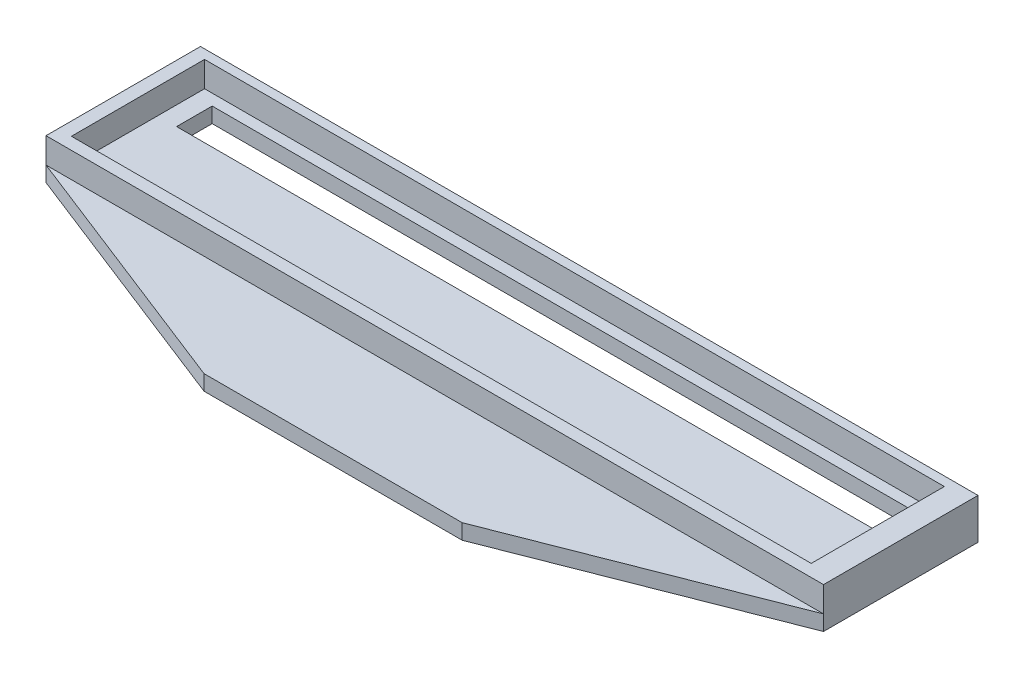
SolidWorks part; units mm, degrees
ref_plane "Alzado" through (0, 0, 0) normal (0, 0, 1) x (1, 0, 0)
ref_plane "Planta" through (0, 0, 0) normal (0, 1, 0) x (1, 0, 0)
ref_plane "Vista lateral" through (0, 0, 0) normal (1, 0, 0) x (0, 0, -1)
sketch "Croquis1" plane through (0, 0, 0) normal (0, 1, 0) x (1, 0, 0)
  line L1 (-38.25, 7.6) -> (38.25, 7.6)
  line L2 (-38.25, 7.6) -> (-38.25, -7.6)
  line L3 (-38.25, -7.6) -> (38.25, -7.6)
  line L4 (38.25, 7.6) -> (38.25, -7.6)
  line L5 (-38.25, 7.6) -> (38.25, -7.6) construction
  line L6 (-38.25, -7.6) -> (38.25, 7.6) construction
  point P0 (0, 0)
  dimension "D1" = 15.2
  dimension "D2" = 76.5
extrude "Saliente-Extruir1" add sketch "Croquis1" along normal blind 4
sketch "Croquis2" plane through (0, 4, 0) normal (0, 1, 0) x (1, 0, 0)
  line L0 (38.25, 7.6) -> (-38.25, 7.6) construction
  line L1 (-38.25, 7.6) -> (-38.25, -7.6) construction
  line L2 (38.25, -7.6) -> (38.25, 7.6) construction
  line L3 (-35.1, 5.6) -> (35.1, 5.6)
  line L4 (-35.1, 5.6) -> (-35.1, 2.1)
  line L5 (-35.1, 2.1) -> (35.1, 2.1)
  line L6 (35.1, 5.6) -> (35.1, 2.1)
  point P6 (0, 0)
  dimension "D1" = 2
  dimension "D2" = 3.5
  dimension "D3" = 3.15
  dimension "D4" = 3.15
extrude "Cortar-Extruir1" cut sketch "Croquis2" against normal blind 4
sketch "Croquis3" plane through (0, 4, 0) normal (0, 1, 0) x (1, 0, 0)
  line L0 (-35.1, 5.6) -> (-35.1, 2.1) construction
  line L1 (-36.95, 6.7) -> (35.8421, 6.7)
  line L2 (-36.95, 6.7) -> (-36.95, -6.4)
  line L3 (-36.95, -6.4) -> (35.8421, -6.4)
  line L4 (35.8421, 6.7) -> (35.8421, -6.4)
  line L5 (35.1, 5.6) -> (-35.1, 5.6) construction
  line L6 (-35.1, 2.1) -> (35.1, 2.1) construction
  dimension "D1" = 1.85
  dimension "D2" = 1.1
  dimension "D3" = 8.5
extrude "Cortar-Extruir2" cut sketch "Croquis3" against normal blind 2.5
sketch "Croquis4" plane through (0, 0, 0) normal (0, 1, 0) x (1, 0, 0)
  line L0 (0, -7.6) -> (0, -17.6) construction
  line L1 (-38.25, -7.6) -> (38.25, -7.6) construction
  line L2 (-12.7, -17.6) -> (12.7, -17.6)
  line L7 (-12.7, -17.6) -> (-38.25, -7.6)
  line L8 (-38.25, -7.6) -> (38.25, -7.6)
  line L9 (38.25, -7.6) -> (12.7, -17.6)
  point P8 (0, -17.6)
  dimension "D1" = 25.4
  dimension "D2" = 10
extrude "Saliente-Extruir2" add sketch "Croquis4" along normal blind 1.5
